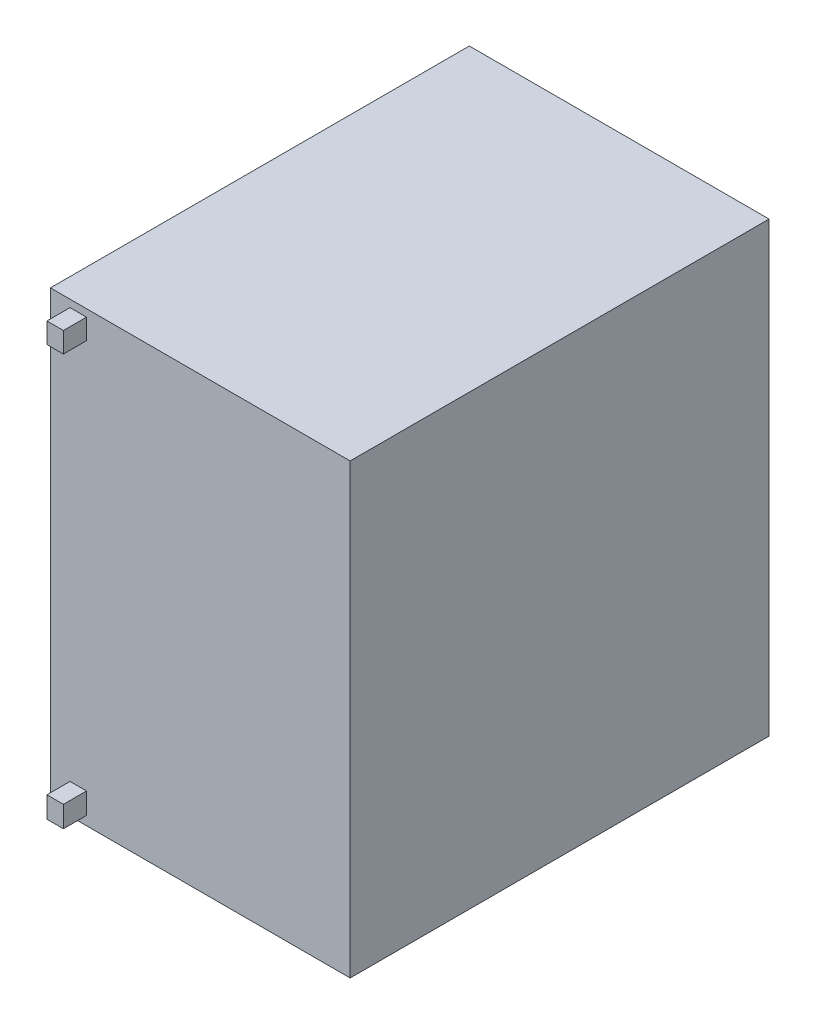
SolidWorks part; units mm, degrees
ref_plane "Front Plane" through (0, 0, 0) normal (0, 0, 1) x (1, 0, 0)
ref_plane "Top Plane" through (0, 0, 0) normal (0, 1, 0) x (1, 0, 0)
ref_plane "Right Plane" through (0, 0, 0) normal (1, 0, 0) x (0, 0, -1)
sketch "Sketch1" plane through (0, 0, 0) normal (0, 1, 0) x (1, 0, 0)
  line L1 (0, 0) -> (-131.7625, 0)
  line L2 (0, 0) -> (0, -184.15)
  line L3 (0, -184.15) -> (-131.7625, -184.15)
  line L4 (-131.7625, 0) -> (-131.7625, -184.15)
  dimension "D1" = 184.15
  dimension "D2" = 131.7625
extrude "Boss-Extrude1" add sketch "Sketch1" along normal blind 196.85
fillet "Fillet1" [suppressed] radius 10
move or copy body "Body-Move/Copy1" bodies to move or copy 101 copy no translate (118.999, -260.35, -108.458)
sketch "Sketch2" plane through (0, 0, 75.692) normal (0, 0, 1) x (1, 0, 0)
  line L1 (-4.1398, -75.6791) -> (3.1033, -75.6791)
  line L2 (-4.1398, -75.6791) -> (-4.1398, -66.7114)
  line L3 (-4.1398, -66.7114) -> (3.1033, -66.7114)
  line L4 (3.1033, -75.6791) -> (3.1033, -66.7114)
  line L5 (-4.1398, -256.4123) -> (3.1033, -256.4123)
  line L6 (-4.1398, -256.4123) -> (-4.1398, -247.0997)
  line L7 (-4.1398, -247.0997) -> (3.1033, -247.0997)
  line L8 (3.1033, -256.4123) -> (3.1033, -247.0997)
extrude "Boss-Extrude2" add sketch "Sketch2" along normal blind 10.16
